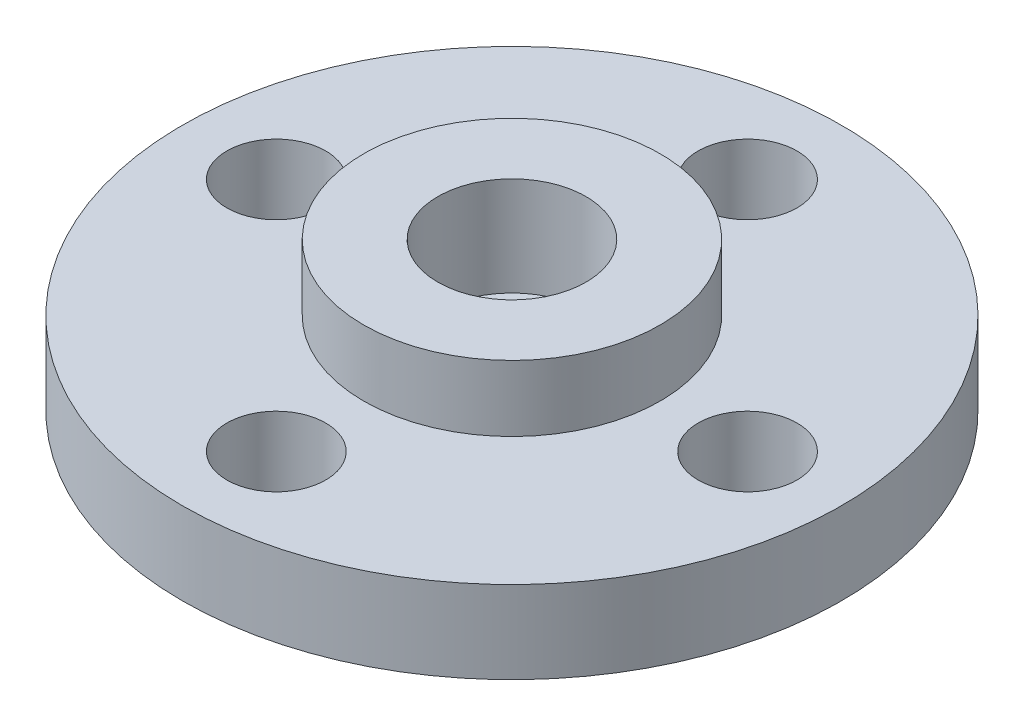
SolidWorks part; units mm, degrees
ref_plane "Front Plane" through (0, 0, 0) normal (0, 0, 1) x (1, 0, 0)
ref_plane "Top Plane" through (0, 0, 0) normal (0, 1, 0) x (1, 0, 0)
ref_plane "Right Plane" through (0, 0, 0) normal (1, 0, 0) x (0, 0, -1)
sketch "Sketch1" plane through (0, 0, 0) normal (0, 1, 0) x (1, 0, 0)
  line L0 (0, 10) -> (0, -10) construction
  line L1 (-10, 0) -> (10, 0) construction
  line L2 (0, 1.5) -> (0, 7.15) construction
  circle A0 centre (0, 0) radius 10
  circle A1 centre (0, 0) radius 1.5
  circle A2 centre (0, 7.15) radius 1.5
  circle A3 centre (7.15, 0) radius 1.5
  circle A4 centre (0, -7.15) radius 1.5
  circle A5 centre (-7.15, 0) radius 1.5
  point P20 (0, 0)
  dimension "D1" = 4
extrude "Boss-Extrude1" add sketch "Sketch1" along normal blind 2.5
sketch "Sketch2" plane through (0, 2.5, 0) normal (0, 1, 0) x (1, 0, 0)
  circle A0 centre (0, 0) radius 4.5
extrude "Boss-Extrude2" add sketch "Sketch2" along normal blind 2
sketch "Sketch3" plane through (0, 4.5, 0) normal (0, 1, 0) x (1, 0, 0)
  circle A3 centre (0, 0) radius 2.25
extrude "Cut-Extrude1" cut sketch "Sketch3" against normal blind 3
